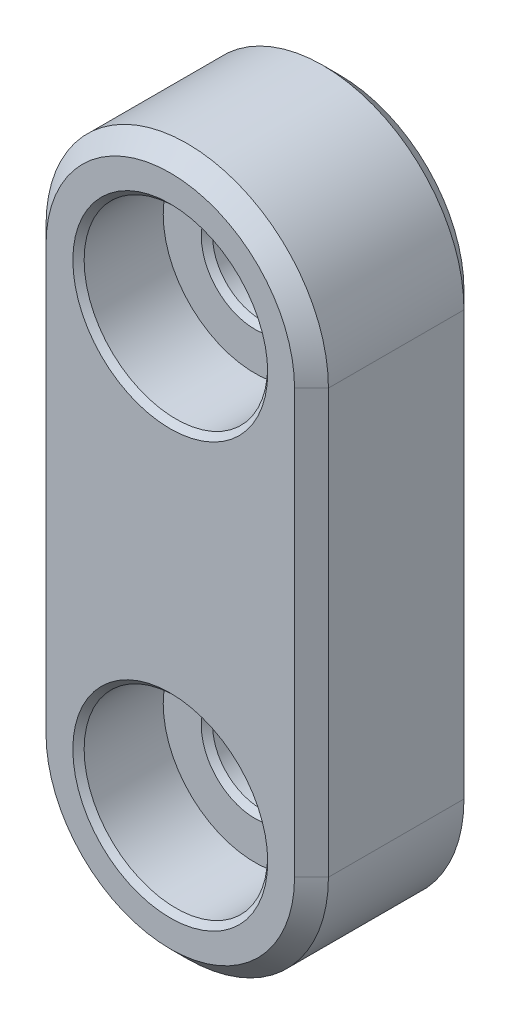
SolidWorks part; units mm, degrees
ref_plane "Front Plane" through (0, 0, 0) normal (0, 0, 1) x (1, 0, 0)
ref_plane "Top Plane" through (0, 0, 0) normal (0, 1, 0) x (1, 0, 0)
ref_plane "Right Plane" through (0, 0, 0) normal (1, 0, 0) x (0, 0, -1)
sketch "Sketch1" plane through (0, 0, 0) normal (0, 0, 1) x (1, 0, 0)
  line L0 (0, -7.5) -> (0, 7.5) construction
  line L1 (-5, -7.5) -> (-5, 7.5)
  line L2 (5, -7.5) -> (5, 7.5)
  arc A0 (-5, -7.5) -> (5, -7.5) centre (0, -7.5) ccw
  arc A1 (5, 7.5) -> (-5, 7.5) centre (0, 7.5) ccw
  point P2 (0, 0)
  dimension "D1" = 10
  dimension "D2" = 15
extrude "Boss-Extrude1" add sketch "Sketch1" along normal blind 6
chamfer "Chamfer1" distance 0.6 angle 45 8 edges at (0, -12.5, 6) (5, 0, 6) (-5, 0, 6) (0, 12.5, 6) (0, -12.5, 0) (5, 0, 0) (-5, 0, 0) (0, 12.5, 0)
sketch "Sketch2" plane through (0, 0, 6) normal (0, 0, 1) x (1, 0, 0)
  point P0 (0, 7.5)
  point P2 (0, -7.5)
hole_wizard "CBORE for M3 SHCS1" positions "Sketch2" profile "Sketch3" counterbore size "M3" standard "ANSI Metric" end condition through all
sketch "Sketch3" plane through (0, 7.5, 6) normal (1, 0, 0) x (0, -1, 0)
  line L0 (0, 0) -> (0, 6)
  line L1 (0, 6) -> (1.7, 6)
  line L3 (1.7, 6) -> (1.7, 3)
  line L4 (1.7, 3) -> (3.25, 3)
  line L5 (3.25, 3) -> (3.25, 0)
  line L7 (3.25, 0) -> (0, 0)
  line L11 (0, -6.35) -> (0, 107.95) construction
  dimension "Thru Hole Dia." = 3.4
  dimension "Thru Hole Depth" = 6
  dimension "C'Bore Dia." = 6.5
  dimension "C'Bore Depth" = 3
chamfer "Deburs" distance 0.2 angle 45 6 edges at (1.7, -7.5, 3) (1.7, -7.5, 0) (1.7, 7.5, 3) (1.7, 7.5, 0) (3.25, 7.5, 6) (3.25, -7.5, 6)
